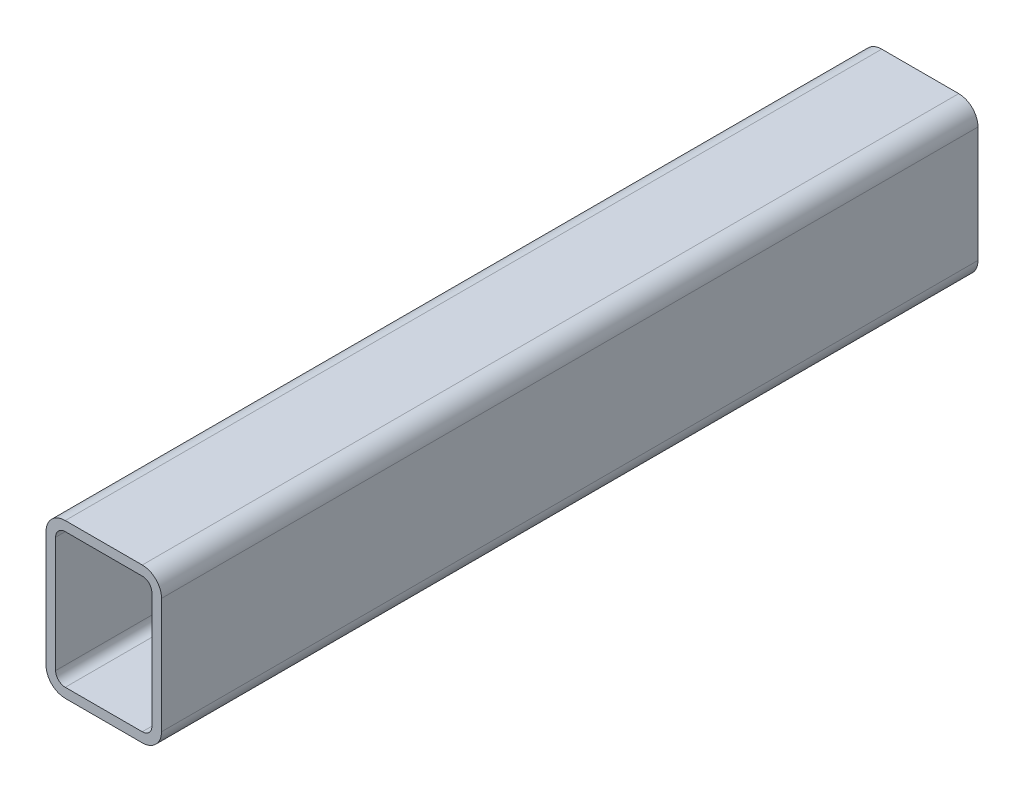
SolidWorks part; units mm, degrees
material "Q355"
ref_plane "前视基准面" through (0, 0, 0) normal (0, 0, 1) x (1, 0, 0)
ref_plane "上视基准面" through (0, 0, 0) normal (0, 1, 0) x (1, 0, 0)
ref_plane "右视基准面" through (0, 0, 0) normal (1, 0, 0) x (0, 0, -1)
sketch "尺寸草图" plane through (0, 0, 0) normal (0, 0, 1) x (1, 0, 0)
  line L0 (-25.8313, 0) -> (25, 0) construction
  line L1 (0, 56.0755) -> (0, -63.3818) construction
  line L2 (-20, 35) -> (20, 35)
  line L3 (-20, 40) -> (20, 40)
  line L4 (-30, 30) -> (-30, -30)
  line L5 (-20, -40) -> (20, -40)
  line L6 (30, 30) -> (30, -30)
  line L7 (25, 30) -> (25, -30)
  line L8 (-20, -35) -> (20, -35)
  line L9 (-25, 30) -> (-25, -30)
  line L10 (-30, 40) -> (-30, -40) construction
  line L11 (-30, -40) -> (30, -40) construction
  line L12 (-25, -35) -> (25, -35) construction
  line L13 (-25, 35) -> (-25, -35) construction
  line L14 (25, 35) -> (25, -35) construction
  line L15 (30, 40) -> (30, -40) construction
  line L16 (-25, 35) -> (25, 35) construction
  line L17 (-30, 40) -> (30, 40) construction
  arc A0 (-30, -30) -> (-20, -40) centre (-20, -30) ccw
  arc A1 (-20, -35) -> (-25, -30) centre (-20, -30) cw
  arc A2 (25, -30) -> (20, -35) centre (20, -30) cw
  arc A3 (20, -40) -> (30, -30) centre (20, -30) ccw
  arc A4 (20, 35) -> (25, 30) centre (20, 30) cw
  arc A5 (20, 40) -> (30, 30) centre (20, 30) cw
  arc A6 (-20, 35) -> (-25, 30) centre (-20, 30) ccw
  arc A7 (-20, 40) -> (-30, 30) centre (-20, 30) ccw
  dimension "D2" = 10
  dimension "H" = 80
  dimension "B" = 60
  dimension "t" = 5
extrude "凸台-拉伸1" add sketch "尺寸草图" along normal mid plane 424
